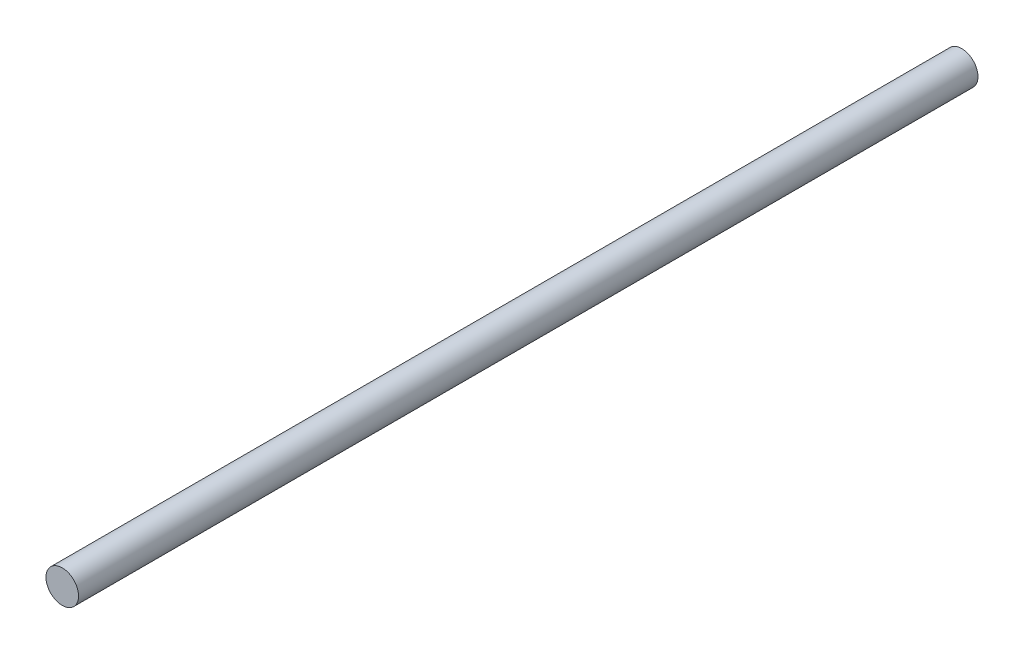
SolidWorks part; units mm, degrees
ref_plane "Front Plane" through (0, 0, 0) normal (0, 0, 1) x (1, 0, 0)
ref_plane "Top Plane" through (0, 0, 0) normal (0, 1, 0) x (1, 0, 0)
ref_plane "Right Plane" through (0, 0, 0) normal (1, 0, 0) x (0, 0, -1)
sketch "Sketch1" plane through (0, 0, 0) normal (0, 0, 1) x (1, 0, 0)
  circle A0 centre (0, 0) radius 3.175
extrude "Boss-Extrude1" add sketch "Sketch1" along normal blind 175.26
